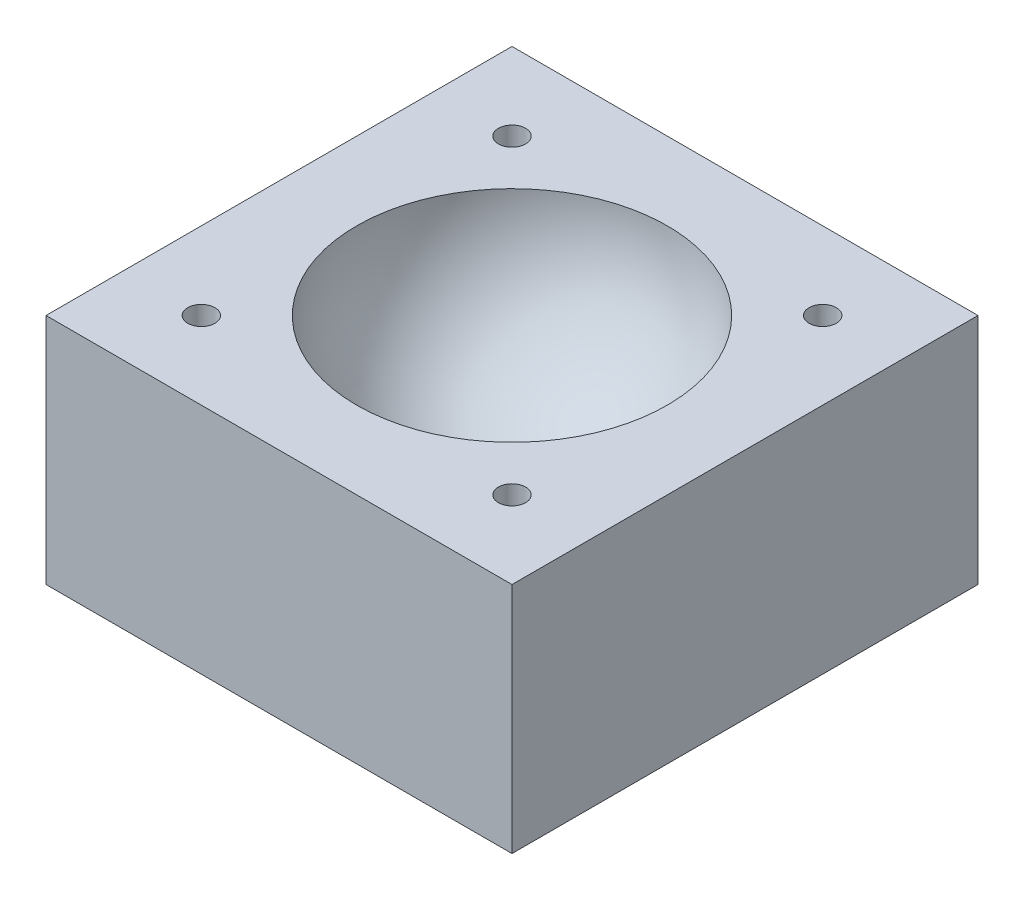
SolidWorks part; units mm, degrees
ref_plane "Front Plane" through (0, 0, 0) normal (0, 0, 1) x (1, 0, 0)
ref_plane "Top Plane" through (0, 0, 0) normal (0, 1, 0) x (1, 0, 0)
ref_plane "Right Plane" through (0, 0, 0) normal (1, 0, 0) x (0, 0, -1)
sketch "Sketch1" plane through (0, 0, 0) normal (0, 1, 0) x (1, 0, 0)
  line L1 (-30, 30) -> (30, 30)
  line L2 (-30, 30) -> (-30, -30)
  line L3 (-30, -30) -> (30, -30)
  line L4 (30, 30) -> (30, -30)
  line L5 (-30, 30) -> (30, -30) construction
  line L6 (-30, -30) -> (30, 30) construction
  point P0 (0, 0)
  dimension "D1" = 60
  dimension "D2" = 60
extrude "Boss-Extrude1" add sketch "Sketch1" along normal blind 30
sketch "Sketch2" plane through (0, 30, 0) normal (0, 1, 0) x (1, 0, 0)
  line L0 (0, 20) -> (0, -20)
  arc A0 (0, -20) -> (0, 20) centre (0, 0) ccw
  point P5 (0, 0)
revolve "Cut-Revolve1" cut sketch "Sketch2" angle 180 about L0
sketch "Sketch3" plane through (0, 30, 0) normal (0, 1, 0) x (1, 0, 0)
  line L0 (-30, 30) -> (-30, -30) construction
  line L1 (30, 30) -> (-30, 30) construction
  line L2 (-30, -30) -> (30, -30) construction
  line L3 (30, -30) -> (30, 30) construction
  circle A0 centre (-20, 20) radius 1.75
  circle A2 centre (-20, -20) radius 1.75
  circle A3 centre (20, 20) radius 1.75
  circle A4 centre (20, -20) radius 1.75
  point P14 (0, 0)
  dimension "D3" = 3.5
  dimension "D4" = 10
  dimension "D5" = 10
  dimension "D1" = 10
  dimension "D2" = 10
  dimension "D6" = 10
  dimension "D7" = 10
extrude "Cut-Extrude1" cut sketch "Sketch3" against normal blind 30
